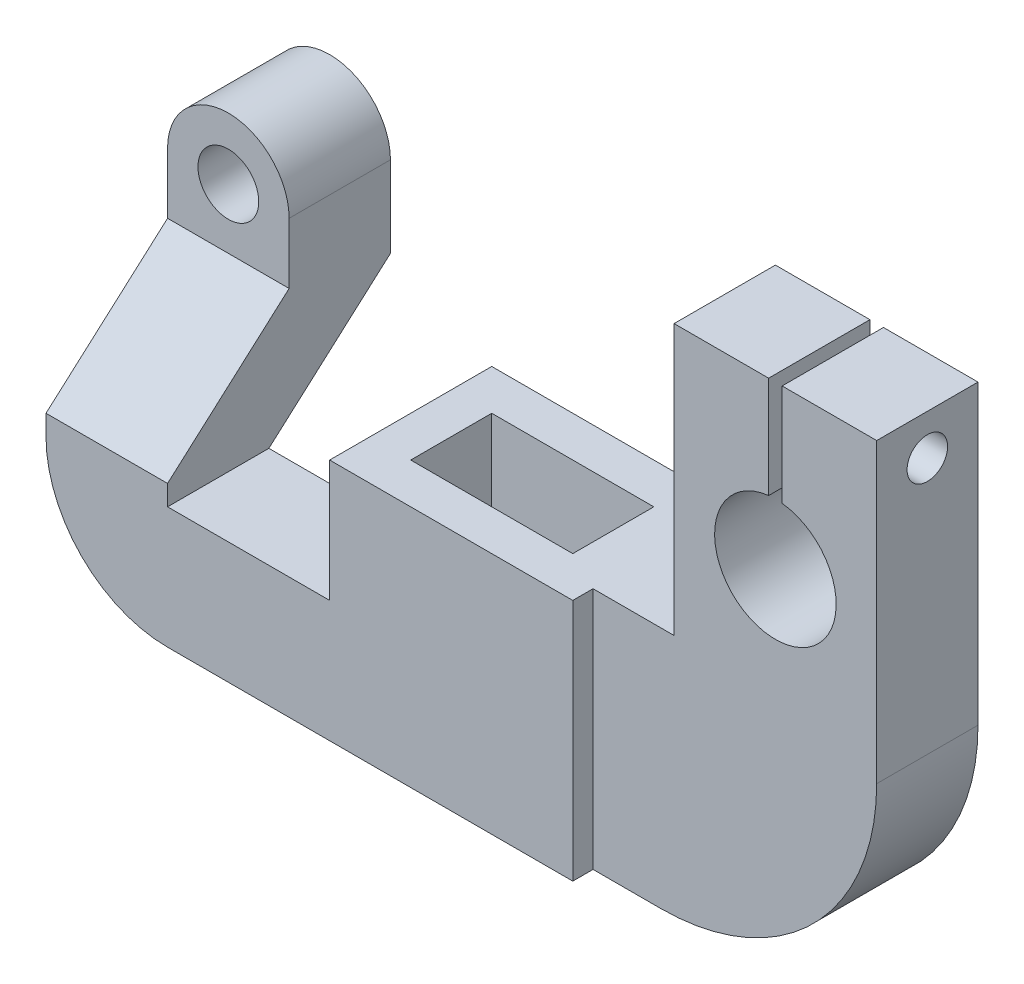
SolidWorks part; units mm, degrees
ref_plane "Front Plane" through (0, 0, 0) normal (0, 0, 1) x (1, 0, 0)
ref_plane "Top Plane" through (0, 0, 0) normal (0, 1, 0) x (1, 0, 0)
ref_plane "Right Plane" through (0, 0, 0) normal (1, 0, 0) x (0, 0, -1)
sketch "Sketch1" plane through (0, 0, 0) normal (0, 0, 1) x (1, 0, 0)
  line L0 (0, 0) -> (12, 0)
  line L1 (12, 0) -> (12, 40)
  line L3 (42, 40) -> (42, -36)
  line L4 (42, -36) -> (0, -36)
  line L5 (0, -36) -> (0, 0)
  line L11 (26, 40) -> (26, 24.9443)
  line L12 (26, 40) -> (12, 40)
  line L13 (28, 40) -> (42, 40)
  line L14 (28, 40) -> (28, 24.9443)
  arc A0 (26, 24.9443) -> (28, 24.9443) centre (27, 16) ccw
  dimension "D5" = 18
  dimension "D1" = 76
  dimension "D2" = 30
  dimension "D3" = 12
  dimension "D4" = 36
  dimension "D6" = 24
extrude "Boss-Extrude1" add sketch "Sketch1" along normal blind 15
sketch "Sketch2" plane through (0, 0, 0) normal (0, 1, 0) x (1, 0, 0)
  line L0 (0, 0) -> (0, 6)
  line L1 (0, 6) -> (-36, 6)
  line L2 (-36, 6) -> (-36, -18)
  line L3 (-36, -18) -> (0, -18)
  line L4 (0, -18) -> (0, -15)
  line L7 (-6, -12) -> (-30, -12)
  line L8 (-6, -12) -> (-6, 0)
  line L9 (-6, 0) -> (-30, 0)
  line L10 (-30, -12) -> (-30, 0)
  line M11 (0, 0) -> (0, -15)
  dimension "D1" = 6
  dimension "D2" = 36
  dimension "D4" = 6
  dimension "6" = 6
extrude "Boss-Extrude2" add sketch "Sketch2" against normal blind 36 contours L3 L4 L0 L1 L2 L7 L10 L9 L8 M11
sketch "Sketch3" plane through (0, 0, 18) normal (0, 0, 1) x (1, 0, 0)
  line L0 (-36, -18) -> (-78, -18)
  line L2 (-36, -36) -> (-36, 0) construction
  line L3 (-78, -18) -> (-78, -36)
  line L4 (-36, -36) -> (-78, -36)
  line L5 (-36, -18) -> (-36, -36)
extrude "Boss-Extrude3" add sketch "Sketch3" against normal blind 15
sketch "Sketch4" plane through (42, 0, 0) normal (1, 0, 0) x (0, 0, -1)
  line L0 (-15, 40) -> (0, 40) construction
  line L1 (0, -36) -> (0, 40) construction
  circle A0 centre (-7.5, 34) radius 3
  dimension "D1" = 6
  dimension "D2" = 6
  dimension "D3" = 7.5
extrude "Cut-Extrude1" cut sketch "Sketch4" against normal blind 34
sketch "Sketch6" plane through (-78, 0, 0) normal (-1, 0, 0) x (0, 0, 1)
  line L0 (3, -18) -> (-15, -2)
  line L1 (-15, -2) -> (-15, 10)
  line L2 (-15, 10) -> (0, 10)
  line L5 (0, 10) -> (0, 1)
  line L7 (18, -18) -> (18, 0) construction
  line L8 (18, -18) -> (18, -15)
  line L9 (18, -18) -> (3, -18)
  line L10 (0, 1) -> (18, -15)
  dimension "D1" = 16
  dimension "D2" = 18
  dimension "D3" = 16
extrude "Boss-Extrude5" add sketch "Sketch6" against normal blind 18
sketch "Sketch7" plane through (0, 0, 0) normal (0, 0, 1) x (1, 0, 0)
  line L0 (-60, 10) -> (-78, 10) construction
  circle A0 centre (-69, 10) radius 9
  dimension "D1" = 18
extrude "Boss-Extrude8" add sketch "Sketch7" against normal up to vertex (15 mm away) up to point (-78, 10, -15)
sketch "Sketch8" plane through (0, 0, 0) normal (0, 0, 1) x (1, 0, 0)
  circle A0 centre (-69.0009, 9.8699) radius 4.5
  arc A4 (-60, 10) -> (-78, 10) centre (-69, 10) ccw construction
  point P2 (0, 0)
  point P3 (0, 0)
  point P4 (0, 0)
  point P7 (0, 0)
  point P8 (0, 0)
  point P9 (0, 0)
  point P10 (-68.6033, 11.2034)
  point P11 (0, 0)
  point P12 (0, 0)
  dimension "D1" = 9
  dimension "D2" = 9
  dimension "D3" = 0.1301
extrude "Cut-Extrude2" cut sketch "Sketch8" against normal through all both and the other way through all
fillet "Fillet1" radius 18 1 edges at (-78, -36, 10.5)
fillet "Fillet2" radius 32 1 edges at (42, -36, 7.5)
